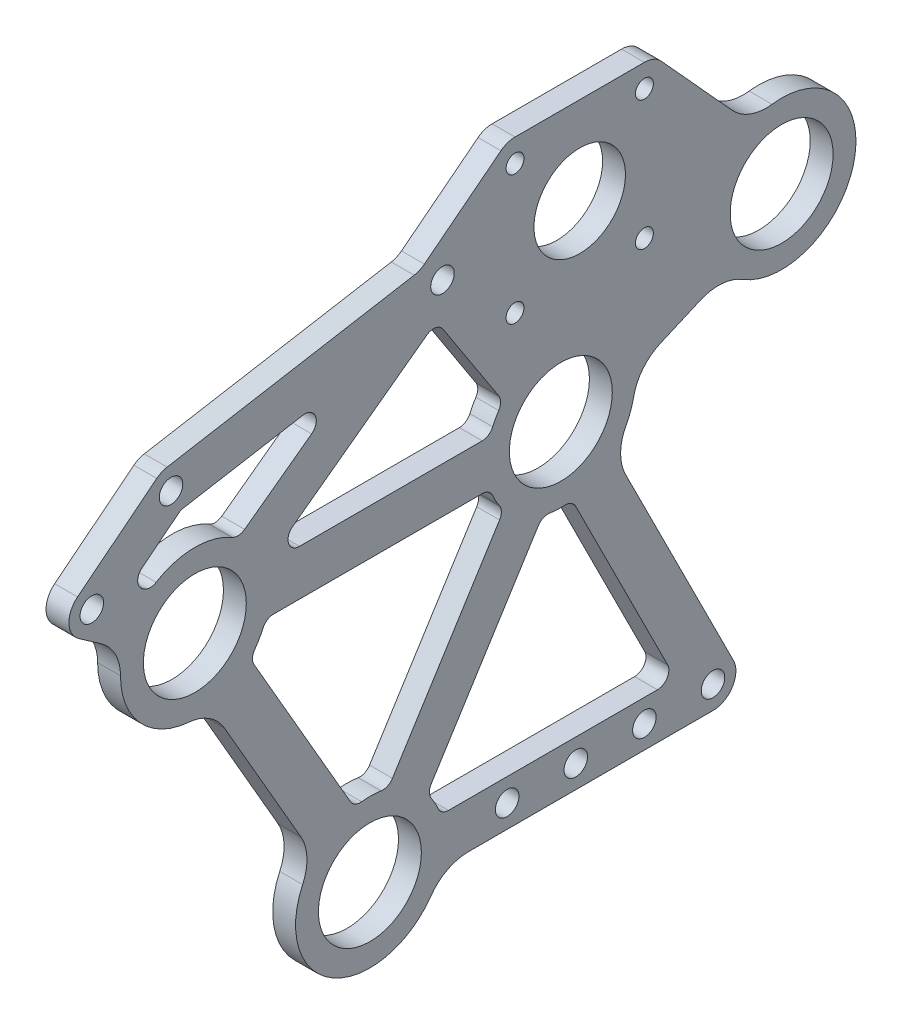
SolidWorks part; units mm, degrees
material "6061-T6 (SS)"
ref_plane "Front Plane" through (0, 0, 0) normal (0, 0, 1) x (1, 0, 0)
ref_plane "Top Plane" through (0, 0, 0) normal (0, 1, 0) x (1, 0, 0)
ref_plane "Right Plane" through (0, 0, 0) normal (1, 0, 0) x (0, 0, -1)
sketch "Sketch1" plane through (0, 0, 0) normal (1, 0, 0) x (0, 0, -1)
  line L0 (-937.5988, 461.4688) -> (-889, 377.2932) construction
  line L1 (-889, 377.2932) -> (-793.75, 377.2932) construction
  line L2 (-793.75, 377.2932) -> (-835.9988, 461.4688) construction
  line L3 (-835.9988, 461.4688) -> (-774.7, 488.0385) construction
  line L4 (-774.7, 488.0385) -> (-868.8544, 511.9974) construction
  line L5 (-868.8544, 511.9974) -> (-944.2148, 498.99) construction
  line L6 (-944.2148, 498.99) -> (-966.2077, 481.5009) construction
  line L7 (-966.2077, 481.5009) -> (-937.5988, 461.4688) construction
  line L8 (-969.8499, 476.2993) -> (-942.3942, 457.0746)
  line L9 (-942.3942, 457.0746) -> (-892.6662, 370.9432)
  line L10 (-892.6662, 370.9432) -> (-793.75, 370.9432)
  line L11 (-788.0747, 380.1417) -> (-827.3104, 458.3139)
  line L12 (-827.3104, 458.3139) -> (-755.1143, 489.607)
  line L14 (-876.7157, 517.0844) -> (-945.2949, 505.2474)
  line L15 (-948.1671, 503.9601) -> (-970.16, 486.471)
  line L16 (-892.6662, 370.9432) -> (-783.4579, 370.9432) construction
  line L17 (-783.4579, 370.9432) -> (-827.3104, 458.3139) construction
  line L18 (-755.1143, 489.607) -> (-868.6004, 518.4851) construction
  line L19 (-868.6004, 518.4851) -> (-946.8956, 504.9711) construction
  line L20 (-946.8956, 504.9711) -> (-976.8167, 481.1775) construction
  line L21 (-976.8167, 481.1775) -> (-942.3942, 457.0746) construction
  line L22 (-868.8544, 511.9974) -> (-848.7149, 529.9579) construction
  line L23 (-848.7149, 529.9579) -> (-812.7939, 529.9579) construction
  line L24 (-812.7939, 529.9579) -> (-774.7, 488.0385) construction
  line L25 (-873.8845, 518.3393) -> (-852.6261, 534.9604)
  line L26 (-848.7149, 536.3079) -> (-812.7939, 536.3079)
  line L27 (-808.0944, 534.2284) -> (-770.0006, 492.309)
  line L28 (-873.0808, 516.7365) -> (-851.1351, 536.3079) construction
  line L29 (-851.1351, 536.3079) -> (-809.9841, 536.3079) construction
  line L30 (-809.9841, 536.3079) -> (-770.0006, 492.309) construction
  circle A0 centre (-774.7, 488.0385) radius 14.2875 construction
  circle A1 centre (-850.9, 377.2932) radius 3.2639 construction
  circle A2 centre (-793.75, 377.2932) radius 3.2639 construction
  circle A3 centre (-812.8, 377.2932) radius 3.2639 construction
  circle A4 centre (-831.85, 377.2932) radius 3.2639 construction
  circle A5 centre (-966.2077, 481.5009) radius 3.2639 construction
  circle A6 centre (-944.2148, 498.99) radius 3.2639 construction
  circle A7 centre (-868.8544, 511.9974) radius 3.2639 construction
  circle A8 centre (-889, 377.2932) radius 14.2875 construction
  circle A9 centre (-835.9988, 461.4688) radius 14.2875 construction
  circle A10 centre (-937.5988, 461.4688) radius 14.2875 construction
  circle A11 centre (-774.7, 488.0385) radius 14.2875
  circle A12 centre (-850.9, 377.2932) radius 3.2639
  circle A13 centre (-793.75, 377.2932) radius 3.2639
  circle A14 centre (-812.8, 377.2932) radius 3.2639
  circle A15 centre (-831.85, 377.2932) radius 3.2639
  circle A16 centre (-966.2077, 481.5009) radius 3.2639
  circle A17 centre (-944.2148, 498.99) radius 3.2639
  circle A18 centre (-868.8544, 511.9974) radius 3.2639
  circle A19 centre (-889, 377.2932) radius 14.2875
  circle A20 centre (-835.9988, 461.4688) radius 14.2875
  circle A21 centre (-937.5988, 461.4688) radius 14.2875
  circle A22 centre (-937.5988, 461.4688) radius 20.6375
  circle A23 centre (-835.9988, 461.4688) radius 20.6375
  circle A24 centre (-889, 377.2932) radius 20.6375
  circle A25 centre (-774.7, 488.0385) radius 20.6375
  arc A26 (-793.75, 370.9432) -> (-788.0747, 380.1417) centre (-793.75, 377.2932) ccw
  arc A28 (-945.2949, 505.2474) -> (-948.1671, 503.9601) centre (-944.2148, 498.99) ccw
  arc A29 (-969.8499, 476.2993) -> (-970.16, 486.471) centre (-966.2077, 481.5009) cw
  circle A30 centre (-848.7149, 529.9579) radius 2.4892 construction
  circle A31 centre (-812.7939, 529.9579) radius 2.4892 construction
  circle A32 centre (-812.7939, 494.0368) radius 2.4892 construction
  circle A33 centre (-848.7149, 494.0368) radius 2.4892 construction
  circle A34 centre (-848.7149, 529.9579) radius 2.4892
  circle A35 centre (-812.7939, 529.9579) radius 2.4892
  circle A36 centre (-812.7939, 494.0368) radius 2.4892
  circle A37 centre (-848.7149, 494.0368) radius 2.4892
  arc A38 (-812.7939, 536.3079) -> (-808.0944, 534.2284) centre (-812.7939, 529.9579) cw
  arc A39 (-852.6261, 534.9604) -> (-848.7149, 536.3079) centre (-848.7149, 529.9579) cw
  arc A40 (-876.7157, 517.0844) -> (-873.8845, 518.3393) centre (-877.7958, 523.3418) ccw
  circle A41 centre (-830.7544, 511.9974) radius 12.7 construction
  circle A42 centre (-830.7544, 511.9974) radius 12.7
  dimension "D4" = 6.35
  dimension "D6" = 6.35
  dimension "D1" = 6.35
  dimension "D5" = 6.35
  dimension "D2" = 6.35
  dimension "D3" = 6.35
extrude "Boss-Extrude1" add sketch "Sketch1" along normal blind 6.35
fillet "Fillet1" radius 12.7 8 edges at (3.175, 506.8413, 783.2066) (3.175, 446.7675, 821.5151) (3.175, 474.403, 790.1913) (3.175, 463.4518, 815.4568) (3.175, 370.9432, 869.3637) (3.175, 391.1237, 904.3174) (3.175, 441.2883, 933.2799) (3.175, 467.5301, 957.3261)
sketch "Sketch2" plane through (6.35, 0, 0) normal (1, 0, 0) x (0, 0, -1)
  line L0 (-937.5988, 461.4688) -> (-835.9988, 461.4688) construction
  line L1 (-835.9988, 461.4688) -> (-868.8544, 511.9974) construction
  line L2 (-868.8544, 511.9974) -> (-937.5988, 461.4688) construction
  line L3 (-903.2266, 486.7331) -> (-944.2148, 498.99) construction
  line L4 (-944.2148, 498.99) -> (-868.8544, 511.9974) construction
  line L5 (-944.2148, 498.99) -> (-966.2077, 481.5009) construction
  line L6 (-966.2077, 481.5009) -> (-937.5988, 461.4688) construction
  line L7 (-943.1347, 492.7325) -> (-867.7743, 505.7399)
  line L8 (-948.1671, 503.9601) -> (-976.8167, 481.1775)
  line L9 (-976.8167, 481.1775) -> (-941.241, 456.2672)
  line L10 (-901.4073, 492.8169) -> (-942.3955, 505.0738)
  line L11 (-872.6152, 517.1139) -> (-941.3596, 466.5853)
  line L12 (-937.5988, 455.1188) -> (-824.2954, 455.1188)
  line L13 (-824.2954, 455.1188) -> (-863.5308, 515.4589)
  line L14 (-945.2949, 505.2474) -> (-869.9344, 518.2548)
  line L15 (-940.2625, 494.0199) -> (-955.5987, 481.8243)
  line L16 (-955.5987, 481.8243) -> (-933.9566, 466.6704)
  line L17 (-905.0459, 480.6493) -> (-946.0341, 492.9061)
  line L18 (-865.0936, 506.8808) -> (-933.838, 456.3522)
  line L19 (-937.5988, 467.8188) -> (-847.7022, 467.8188)
  line L20 (-847.7022, 467.8188) -> (-874.1779, 508.5358)
  line L21 (-937.5988, 461.4688) -> (-889, 377.2932) construction
  line L22 (-889, 377.2932) -> (-835.9988, 461.4688) construction
  line L23 (-835.9988, 461.4688) -> (-793.75, 377.2932) construction
  line L24 (-793.75, 377.2932) -> (-889, 377.2932) construction
  line L25 (-943.0981, 458.2938) -> (-894.4993, 374.1182)
  line L26 (-900.5022, 370.9432) -> (-835.3737, 474.3791)
  line L27 (-835.3737, 474.3791) -> (-783.4579, 370.9432)
  line L28 (-783.4579, 370.9432) -> (-900.5022, 370.9432)
  line L29 (-932.0995, 464.6438) -> (-883.5007, 380.4682)
  line L30 (-877.4978, 383.6432) -> (-836.6239, 448.5584)
  line L31 (-836.6239, 448.5584) -> (-804.0421, 383.6432)
  line L32 (-804.0421, 383.6432) -> (-877.4978, 383.6432)
  line L33 (-903.4713, 478.6724) -> (-910.4376, 473.5521)
  circle A0 centre (-966.2077, 481.5009) radius 6.35
  circle A1 centre (-944.2148, 498.99) radius 6.35
  circle A2 centre (-937.5988, 461.4688) radius 20.6375
  circle A3 centre (-868.8544, 511.9974) radius 6.35
  circle A4 centre (-835.9988, 461.4688) radius 20.6375
  circle A5 centre (-889, 377.2932) radius 20.6375
  arc A6 (-910.4376, 473.5521) -> (-908.5572, 467.8188) centre (-908.5572, 470.9938) ccw
  point P55 (-903.4713, 478.6724)
  dimension "D1" = 41.275
  dimension "D2" = 12.7
  dimension "D7" = 3.175
  dimension "D5" = 6.35
  dimension "D3" = 6.35
  dimension "D4" = 6.35
  dimension "D6" = 6.35
extrude "Cut-Extrude1" cut sketch "Sketch2" against normal through all contours A2 L11 L17 L15 L16 | L11 L7 L10 | A4 L20 L18 A2 L19 | A5 L26 A4 L12 A2 L29 | A5 L32 L31 A4 L30 | L17 L11 L10 L7 L15
fillet "Fillet2" radius 3.175 19 edges at (3.175, 383.6432, 804.0421) (3.175, 441.4686, 841.088) (3.175, 441.0705, 832.8656) (3.175, 448.2355, 851.8351) (3.175, 455.1188, 855.6351) (3.175, 390.5265, 873.1637) (3.175, 383.6432, 869.3637) (3.175, 397.2933, 883.9108) (3.175, 397.4737, 893.3189) (3.175, 455.1188, 917.9625) (3.175, 447.6383, 922.2814) (3.175, 493.0088, 941.534) (3.175, 481.8243, 955.5987) (3.175, 477.9333, 950.0417) (3.175, 478.2149, 925.5375) (3.175, 501.1573, 894.3242) (3.175, 502.8981, 870.5121) (3.175, 467.8188, 855.6351) (3.175, 474.4694, 852.0266)
